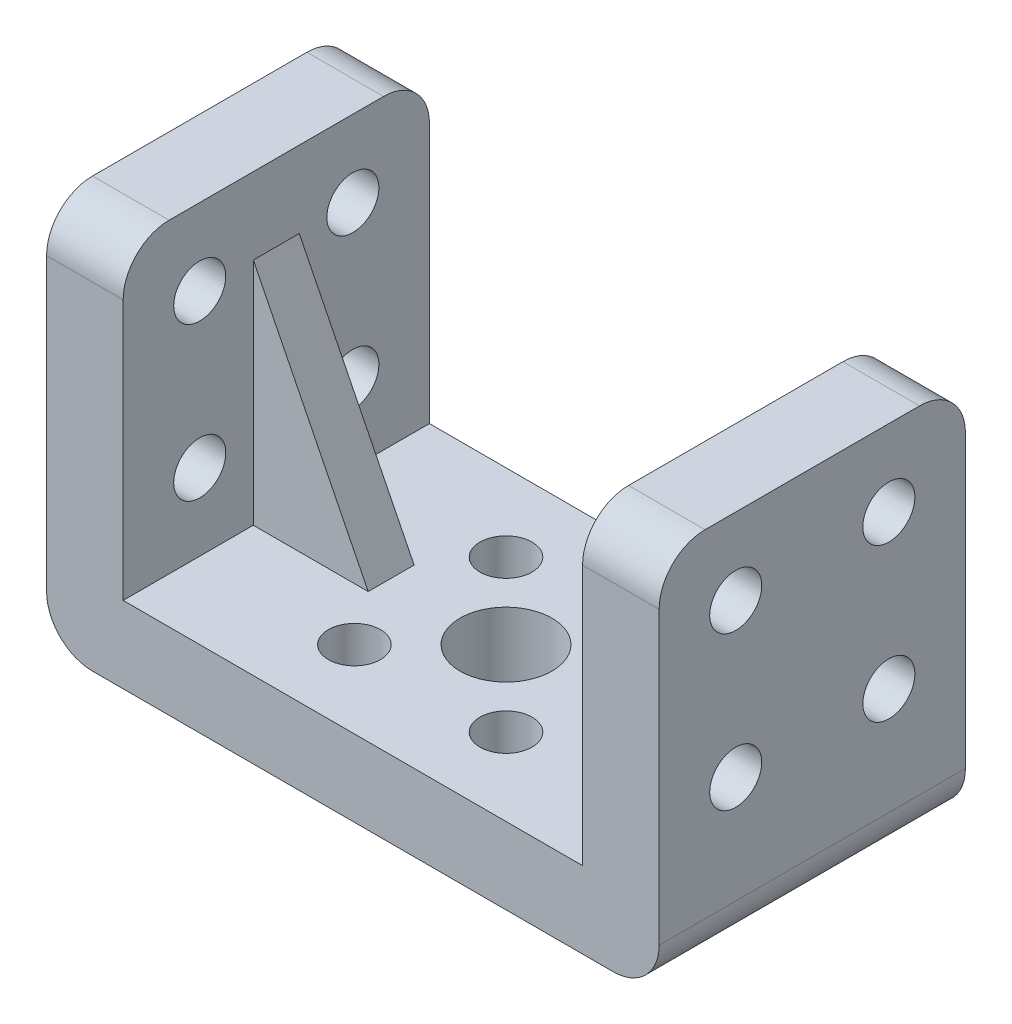
SolidWorks part; units mm, degrees
ref_plane "前视基准面" through (0, 0, 0) normal (0, 0, 1) x (1, 0, 0)
ref_plane "上视基准面" through (0, 0, 0) normal (0, 1, 0) x (1, 0, 0)
ref_plane "右视基准面" through (0, 0, 0) normal (1, 0, 0) x (0, 0, -1)
sketch "草图1" plane through (0, 0, 0) normal (0, 1, 0) x (1, 0, 0)
  line L0 (0, 0) -> (4.9497, 4.9497) construction
  line L1 (-20, -10) -> (20, -10)
  line L2 (-20, -10) -> (-20, 10)
  line L3 (-20, 10) -> (20, 10)
  line L4 (20, -10) -> (20, 10)
  line L5 (-20, -10) -> (20, 10) construction
  line L6 (-20, 10) -> (20, -10) construction
  circle A0 centre (0, 0) radius 7 construction
  circle A1 centre (4.9497, 4.9497) radius 1.7
  circle A2 centre (4.9497, -4.9497) radius 1.7
  circle A3 centre (-4.9497, -4.9497) radius 1.7
  circle A4 centre (-4.9497, 4.9497) radius 1.7
  circle A5 centre (0, 0) radius 3
  point P0 (0, 0)
  point P19 (0, 0)
  dimension "D3" = 14
  dimension "D4" = 3.4
  dimension "D7" = 6
  dimension "D1" = 40
  dimension "D2" = 20
  dimension "D5" = 45
  dimension "D6" = 4
extrude "凸台-拉伸1" add sketch "草图1" along normal blind 5
sketch "草图2" plane through (0, 5, 0) normal (0, 1, 0) x (1, 0, 0)
  line L0 (-20, -10) -> (20, -10) construction
  line L1 (-20, 10) -> (-15, 10)
  line L2 (-20, 10) -> (-20, -10)
  line L3 (-20, -10) -> (-15, -10)
  line L4 (-15, 10) -> (-15, -10)
  line L6 (20, 10) -> (15, 10)
  line L7 (20, 10) -> (20, -10)
  line L8 (20, -10) -> (15, -10)
  line L9 (15, 10) -> (15, -10)
  dimension "D1" = 5
extrude "凸台-拉伸2" add sketch "草图2" along normal blind 20
sketch "草图3" plane through (0, 0, 0) normal (0, 0, 1) x (1, 0, 0)
  line L0 (-15, 20) -> (-7.5, 5)
  line L1 (-7.5, 5) -> (-15, 5)
  line L2 (-15, 5) -> (-15, 20)
  line L3 (-15, 25) -> (-15, 5) construction
  line L4 (6.6497, 5) -> (3.2497, 5) construction
  line L6 (0, -11) -> (0, 11) construction
  line L7 (15, 5) -> (15, 20)
  line L8 (7.5, 5) -> (15, 5)
  line L9 (15, 20) -> (7.5, 5)
  dimension "D1" = 15
  dimension "D2" = 7.5
extrude "凸台-拉伸3" add sketch "草图3" along normal blind 1.5 and the other way blind 1.5
sketch "草图4" plane through (-20, 0, 0) normal (-1, 0, 0) x (0, 0, 1)
  line L0 (0, 25) -> (0, 15) construction
  line L1 (-10, 25) -> (10, 25) construction
  line L3 (-5, 10) -> (5, 10) construction
  line L4 (-5, 10) -> (-5, 20) construction
  line L5 (-5, 20) -> (5, 20) construction
  line L6 (5, 10) -> (5, 20) construction
  line L7 (-5, 10) -> (5, 20) construction
  line L8 (-5, 20) -> (5, 10) construction
  circle A0 centre (-5, 20) radius 1.7
  circle A1 centre (5, 20) radius 1.7
  circle A2 centre (5, 10) radius 1.7
  circle A3 centre (-5, 10) radius 1.7
  dimension "D4" = 3.4
  dimension "D3" = 10
extrude "切除-拉伸1" cut sketch "草图4" against normal through all
fillet "圆角1" radius 3 6 edges at (-20, 0, 0) (20, 0, 0) (17.5, 25, 10) (17.5, 25, -10) (-17.5, 25, -10) (-17.5, 25, 10)
